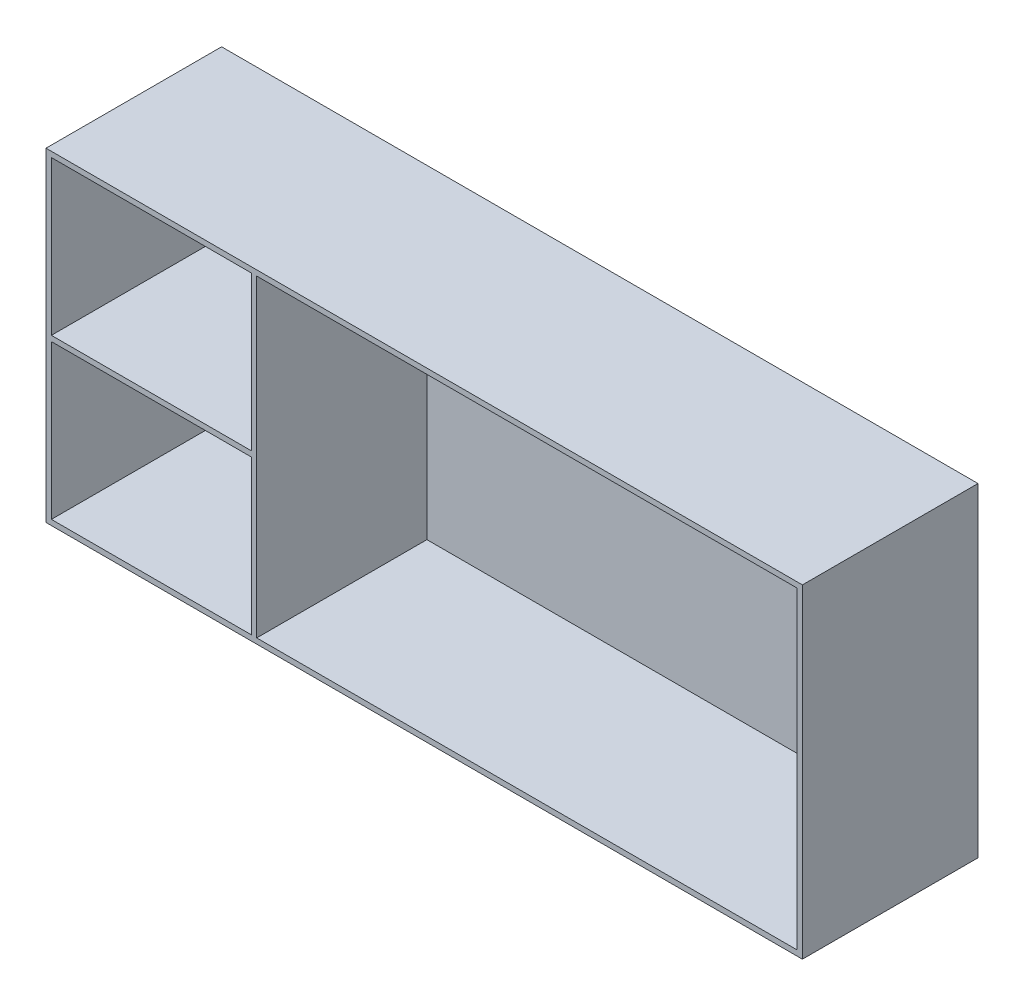
SolidWorks part; units mm, degrees
ref_plane "Přední rovina" through (0, 0, 0) normal (0, 0, 1) x (1, 0, 0)
ref_plane "Horní rovina" through (0, 0, 0) normal (0, 1, 0) x (1, 0, 0)
ref_plane "Pravá rovina" through (0, 0, 0) normal (1, 0, 0) x (0, 0, -1)
sketch "Skica1" plane through (0, 0, 0) normal (0, 0, 1) x (1, 0, 0)
  line L1 (140, 60) -> (-140, 60)
  line L2 (140, 60) -> (140, -60)
  line L3 (140, -60) -> (-140, -60)
  line L4 (-140, 60) -> (-140, -60)
  line L5 (140, 60) -> (-140, -60) construction
  line L6 (140, -60) -> (-140, 60) construction
  point P0 (0, 0)
  dimension "D1" = 280
  dimension "D2" = 120
extrude "Přidat vysunutím1" add sketch "Skica1" along normal blind 65
sketch "Skica2" plane through (0, 0, 65) normal (0, 0, 1) x (1, 0, 0)
  line L0 (-64, 0) -> (-138, 0)
  line L1 (-138, 58) -> (138, 58)
  line L2 (-138, 58) -> (-138, -58)
  line L3 (-138, -58) -> (138, -58)
  line L4 (138, 58) -> (138, -58)
  line L5 (-138, 58) -> (138, -58) construction
  line L6 (-138, -58) -> (138, 58) construction
  line L7 (-64, -58) -> (-62, -58)
  line L8 (-64, -58) -> (-64, 58)
  line L9 (-64, 58) -> (-62, 58)
  line L10 (-62, -58) -> (-62, 58)
  line L12 (-138, 1) -> (-64, 1)
  line L13 (-138, 1) -> (-138, -1)
  line L14 (-138, -1) -> (-64, -1)
  line L15 (-64, 1) -> (-64, -1)
  line L16 (-138, 1) -> (-64, -1) construction
  line L17 (-138, -1) -> (-64, 1) construction
  point P0 (0, 0)
  point P12 (-101, 0)
  dimension "D1" = 276
  dimension "D2" = 116
  dimension "D3" = 200
  dimension "D4" = 2
  dimension "D5" = 2
extrude "Odebrat vysunutím1" cut sketch "Skica2" against normal blind 63 contours L14 L2 L3 L8 | L2 L12 L8 L1 | L10 L3 L4 L1
